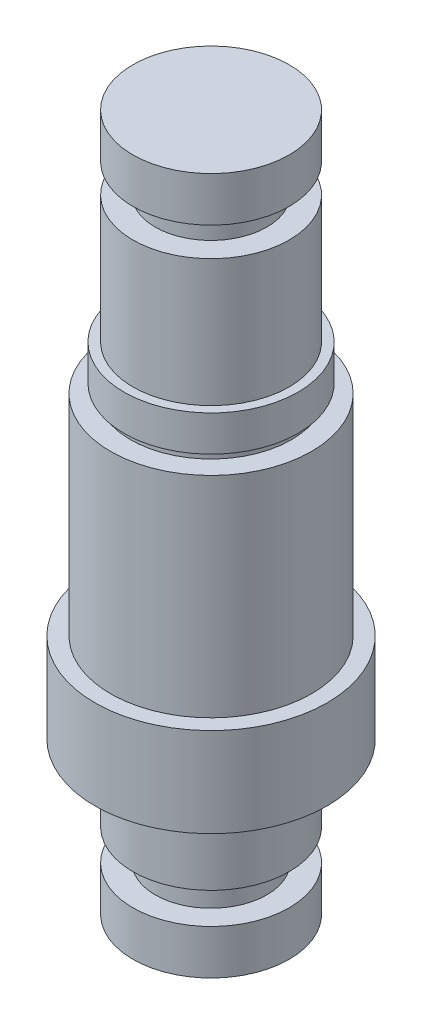
SolidWorks part; units mm, degrees
ref_plane "前视基准面" through (0, 0, 0) normal (0, 0, 1) x (1, 0, 0)
ref_plane "上视基准面" through (0, 0, 0) normal (0, 1, 0) x (1, 0, 0)
ref_plane "右视基准面" through (0, 0, 0) normal (1, 0, 0) x (0, 0, -1)
sketch "草图1" plane through (0, 0, 0) normal (0, 0, 1) x (1, 0, 0)
  line L0 (0, -1000) -> (0, 49000) construction
  line L1 (0, 0) -> (0, 156)
  line L2 (0, 156) -> (17.5, 156)
  line L3 (17.5, 156) -> (17.5, 146)
  line L4 (17.5, 146) -> (12.5, 146)
  line L5 (12.5, 146) -> (12.5, 139.5)
  line L6 (12.5, 139.5) -> (17.5, 139.5)
  line L7 (17.5, 139.5) -> (17.5, 111)
  line L8 (17.5, 111) -> (19.5, 111)
  line L9 (19.5, 111) -> (19.5, 103)
  line L10 (19.5, 103) -> (18, 103)
  line L11 (18, 103) -> (18, 101)
  line L12 (18, 101) -> (22.5, 101)
  line L14 (0, 0) -> (17.5, 0)
  line L15 (17.5, 0) -> (17.5, 10)
  line L16 (17.5, 10) -> (12.5, 10)
  line L17 (12.5, 10) -> (12.5, 17)
  line L18 (12.5, 17) -> (17.5, 17)
  line L19 (17.5, 17) -> (17.5, 34)
  line L20 (17.5, 34) -> (26, 34)
  line L21 (26, 34) -> (26, 54)
  line L22 (26, 54) -> (22.5, 54)
  line L23 (22.5, 54) -> (22.5, 101)
  dimension "D1" = 17.5
  dimension "D2" = 156
  dimension "D3" = 10
  dimension "D4" = 12.5
  dimension "D5" = 6.5
  dimension "D6" = 17.5
  dimension "D7" = 28.5
  dimension "D8" = 19.5
  dimension "D9" = 8
  dimension "D10" = 17.5
  dimension "D11" = 10
  dimension "D12" = 12.5
  dimension "D13" = 7
  dimension "D14" = 17.5
  dimension "D15" = 17
  dimension "D16" = 26
  dimension "D17" = 20
  dimension "D18" = 22.5
  dimension "D19" = 47
  dimension "D20" = 18
revolve "旋转1" add sketch "草图1" angle 360 about L0
